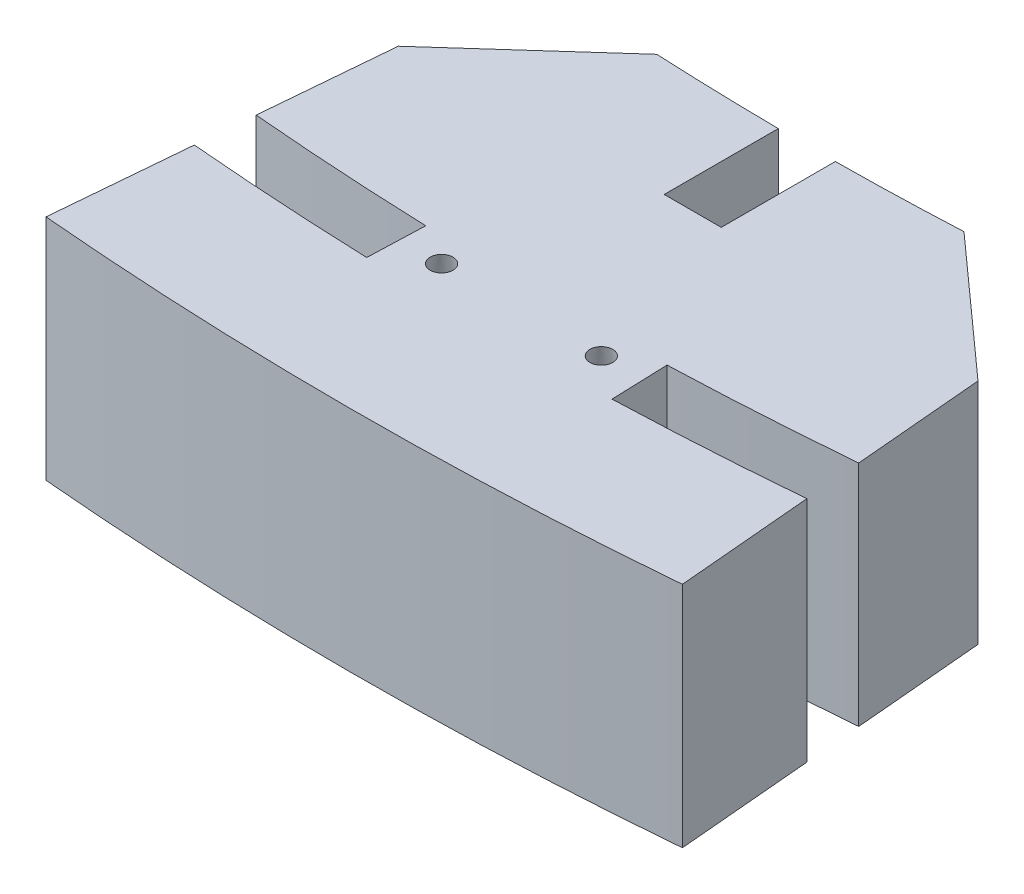
SolidWorks part; units mm, degrees
ref_plane "前视基准面" through (0, 0, 0) normal (0, 0, 1) x (1, 0, 0)
ref_plane "上视基准面" through (0, 0, 0) normal (0, 1, 0) x (1, 0, 0)
ref_plane "右视基准面" through (0, 0, 0) normal (1, 0, 0) x (0, 0, -1)
sketch "草图3" plane through (0, 0, 0) normal (0, 1, 0) x (1, 0, 0)
  line L0 (0, -1400) -> (0, -1600) construction
  line L3 (-139.4492, -1593.9115) -> (-122.018, -1394.6726)
  line L4 (122.018, -1394.6726) -> (139.4492, -1593.9115)
  arc A0 (-122.018, -1394.6726) -> (122.018, -1394.6726) centre (0, 0) ccw
  arc A1 (-139.4492, -1593.9115) -> (139.4492, -1593.9115) centre (0, 0) ccw
  dimension "D1" = 5
  dimension "D2" = 5
extrude "凸台-拉伸1" add sketch "草图3" along normal blind 100
sketch "草图6" plane through (0, 100, 0) normal (0, 1, 0) x (1, 0, 0)
  line L0 (0, 0) -> (0, -1600) construction
  line L1 (-12.5, -1399.9442) -> (12.5, -1399.9442)
  line L2 (0, -1449.9442) -> (12.5, -1449.9442)
  line L3 (12.5, -1449.9442) -> (12.5, -1399.9442)
  line L4 (0, -1449.9442) -> (-12.5, -1449.9442)
  line L5 (-12.5, -1449.9442) -> (-12.5, -1399.9442)
  arc A0 (-139.4492, -1593.9115) -> (139.4492, -1593.9115) centre (0, 0) ccw construction
  arc A1 (-122.018, -1394.6726) -> (122.018, -1394.6726) centre (0, 0) ccw construction
  dimension "D1" = 12.5
  dimension "D2" = 12.5
  dimension "D3" = 50
extrude "切除-拉伸2" cut sketch "草图6" against normal through all
sketch "草图7" plane through (0, 100, 0) normal (0, 1, 0) x (1, 0, 0)
  line L0 (0, 0) -> (0, -1600) construction
  line L1 (0, 0) -> (966.7868, 0)
  line L2 (10, -1500) -> (60, -1500)
  line L3 (10, -1500) -> (10, -1550)
  line L4 (10, -1550) -> (60, -1550)
  line L5 (60, -1500) -> (60, -1550)
  line L6 (10, -1500) -> (60, -1550) construction
  line L7 (10, -1550) -> (60, -1500) construction
  line L8 (-60, -1500) -> (-10, -1500)
  line L9 (-60, -1500) -> (-60, -1550)
  line L10 (-60, -1550) -> (-10, -1550)
  line L11 (-10, -1500) -> (-10, -1550)
  line L12 (-60, -1500) -> (-10, -1550) construction
  line L13 (-60, -1550) -> (-10, -1500) construction
  arc A0 (-139.4492, -1593.9115) -> (139.4492, -1593.9115) centre (0, 0) ccw construction
  point P6 (35, -1525)
  point P11 (-35, -1525)
  point P16 (-10, -1525)
  dimension "D1" = 50
  dimension "D2" = 50
  dimension "D3" = 50
  dimension "D4" = 50
  dimension "D5" = 10
  dimension "D6" = 10
  dimension "D7" = 1500
  dimension "D8" = 1500
ref_plane "基准面1" through (-35, 0, 0) normal (1, 0, 0) x (0, 0, -1)
sketch "草图8" plane through (-35, 0, 0) normal (1, 0, 0) x (0, 0, -1)
  line L0 (-1525, 100) -> (-1530, 100)
  line L1 (-1530, 100) -> (-1538.6824, 50.7596)
  line L2 (-1538.6824, 50.7596) -> (-1538.6824, 0)
  line L3 (-1538.6824, 0) -> (-1525, 0)
  line L4 (-1525, 0) -> (-1525, 100)
  dimension "D1" = 5
  dimension "D2" = 50
  dimension "D3" = 100
  dimension "D4" = 100
revolve "切除-旋转1" cut sketch "草图8" angle 360 about L4
ref_plane "基准面2" through (0, 0, 0) normal (-1, 0, 0) x (0, 0, 1)
mirror "镜向1" about plane through (0, 0, 0) normal (-1, 0, 0) of "切除-旋转1"
sketch "草图10" plane through (0, 0, 0) normal (0, -1, 0) x (1, 0, 0)
  line L0 (-134.2198, 1534.1398) -> (-132.041, 1509.235)
  line L3 (-53.7452, 1539.0619) -> (-52.8727, 1514.0771)
  line L5 (-52.8727, 1514.0771) -> (0, 0) construction
  line L6 (-122.018, 1394.6726) -> (-139.4492, 1593.9115) construction
  line L7 (0, 1600) -> (0, 0) construction
  line L8 (53.7452, 1539.0619) -> (52.8727, 1514.0771)
  line L9 (134.2198, 1534.1398) -> (132.041, 1509.235)
  arc A2 (-52.8727, 1514.0771) -> (-132.041, 1509.235) centre (0, 0) ccw
  arc A3 (-53.7452, 1539.0619) -> (-134.2198, 1534.1398) centre (0, 0) ccw
  arc A4 (53.7452, 1539.0619) -> (134.2198, 1534.1398) centre (0, 0) cw
  arc A5 (52.8727, 1514.0771) -> (132.041, 1509.235) centre (0, 0) cw
  dimension "D1" = 1515
  dimension "D2" = 1540
  dimension "D5" = 3
extrude "切除-拉伸7" cut sketch "草图10" against normal through all
sketch "草图11" plane through (0, 0, 0) normal (-0.9994, 0, -0.0349) x (-0.0349, 0, 0.9994)
  line L1 (1534, 45) -> (1519, 45)
  line L2 (1534, 45) -> (1534, 35)
  line L3 (1534, 35) -> (1519, 35)
  line L4 (1519, 45) -> (1519, 35)
  line L5 (1534, 45) -> (1519, 35) construction
  line L6 (1534, 35) -> (1519, 45) construction
  line L7 (1515, 100) -> (1515, 0) construction
  line L8 (1515, 100) -> (1540, 100) construction
  point P0 (1526.5, 40)
  dimension "D1" = 15
  dimension "D2" = 10
  dimension "D3" = 60
  dimension "D4" = 4
hole_wizard "M6 螺纹孔的螺纹孔钻头1" positions "草图12" profile "草图13" hole size "M6" standard "GB"
sketch "草图12" plane through (0, 0, 0) normal (-0.9994, 0, -0.0349) x (-0.0349, 0, 0.9994)
  point P0 (1526.5, 40)
sketch "草图13" plane through (-53.2741, 40, 1525.5701) normal (0, 1, 0) x (-0.0349, 0, 0.9994)
  line L0 (0, 0) -> (0, 4.614)
  line L1 (0, 4.614) -> (2.5, 4.614)
  line L2 (2.5, 4.614) -> (2.5, 0)
  line L5 (2.5, 0) -> (0, 0)
  line L11 (0, -6.35) -> (0, 107.95) construction
  dimension "通孔孔直径" = 5
  dimension "通孔孔深度" = 4.614
mirror "镜向2" about plane through (0, 0, 0) normal (-1, 0, 0) of "M6 螺纹孔的螺纹孔钻头1"
sketch "草图14" plane through (0, 0, 0) normal (0, -1, 0) x (1, 0, 0)
  line L0 (0, 1600) -> (0, 1449.9442) construction
  line L2 (127.0295, 1451.9538) -> (67.3106, 1398.3809)
  line L3 (132.041, 1509.235) -> (122.018, 1394.6726) construction
  line L4 (127.0295, 1451.9538) -> (122.018, 1394.6726)
  line L5 (-12.5, 1449.9442) -> (12.5, 1449.9442) construction
  line L6 (-127.0295, 1451.9538) -> (-122.018, 1394.6726)
  line L7 (-127.0295, 1451.9538) -> (-67.3106, 1398.3809)
  arc A1 (122.018, 1394.6726) -> (12.5, 1399.9442) centre (0, 0) ccw construction
  arc A2 (67.3106, 1398.3809) -> (122.018, 1394.6726) centre (0, 0) cw
  arc A3 (-67.3106, 1398.3809) -> (-122.018, 1394.6726) centre (0, 0) ccw
extrude "切除-拉伸8" cut sketch "草图14" against normal up to next
